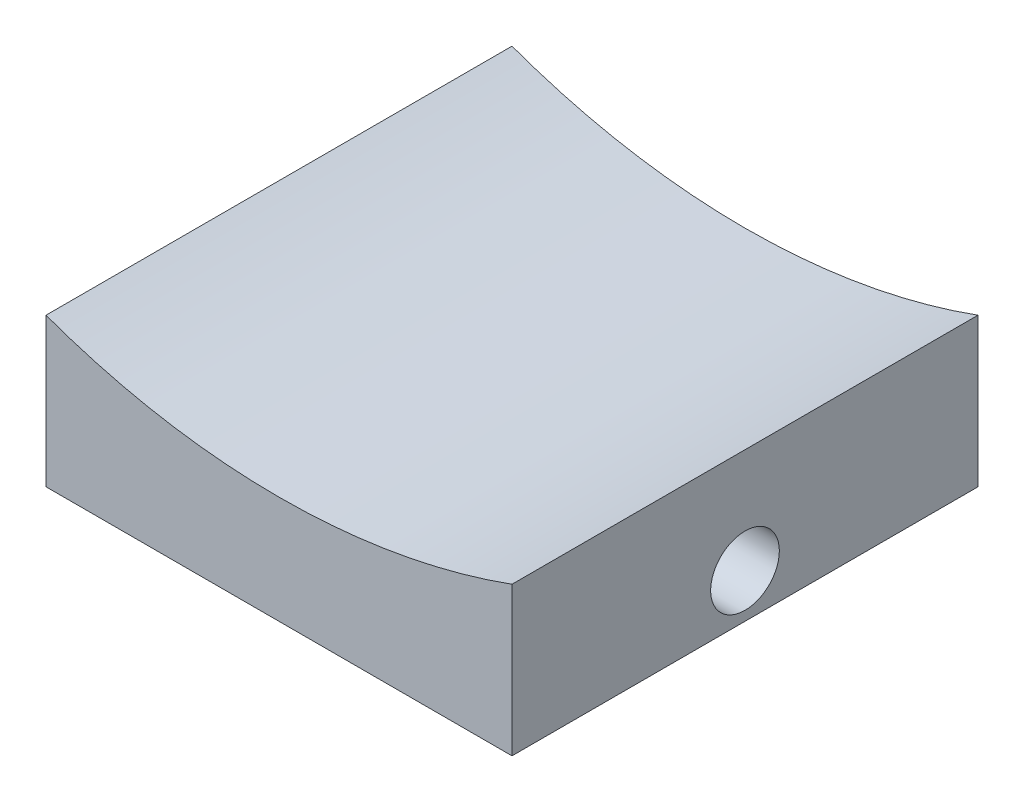
SolidWorks part; units mm, degrees
ref_plane "Ebene vorne" through (0, 0, 0) normal (0, 0, 1) x (1, 0, 0)
ref_plane "Ebene oben" through (0, 0, 0) normal (0, 1, 0) x (1, 0, 0)
ref_plane "Ebene rechts" through (0, 0, 0) normal (1, 0, 0) x (0, 0, -1)
sketch "Skizze1" plane through (0, 0, 0) normal (0, 0, 1) x (1, 0, 0)
  line L1 (-32.5, 15) -> (32.5, 15)
  line L2 (-32.5, 15) -> (-32.5, -15)
  line L3 (-32.5, -15) -> (32.5, -15)
  line L4 (32.5, 15) -> (32.5, -15)
  dimension "D1" = 30
  dimension "D2" = 65
  dimension "D3" = 32.5
  dimension "D4" = 15
extrude "Aufsatz-Linear austragen1" add sketch "Skizze1" along normal blind 65
sketch "Skizze2" plane through (0, 0, 65) normal (0, 0, 1) x (1, 0, 0)
  line L0 (-32.5, -15) -> (32.5, -15) construction
  circle A0 centre (0, 95) radius 95
  dimension "D1" = 110
extrude "Schnitt-Linear austragen1" cut sketch "Skizze2" against normal up to vertex (65 mm away) up to point (0, 0, 0)
sketch "Skizze5" plane through (32.5, 0, 0) normal (1, 0, 0) x (0, 0, -1)
  line L0 (-65, -15) -> (-65, 5.7321) construction
  line L1 (-65, -15) -> (0, -15) construction
  circle A0 centre (-32.5, -8.88) radius 4.79
  point P6 (0, 0)
  dimension "D3" = 9.58
  dimension "D1" = 32.5
  dimension "D2" = 6.12
extrude "Schnitt-Linear austragen2" cut sketch "Skizze5" against normal blind 34.98
